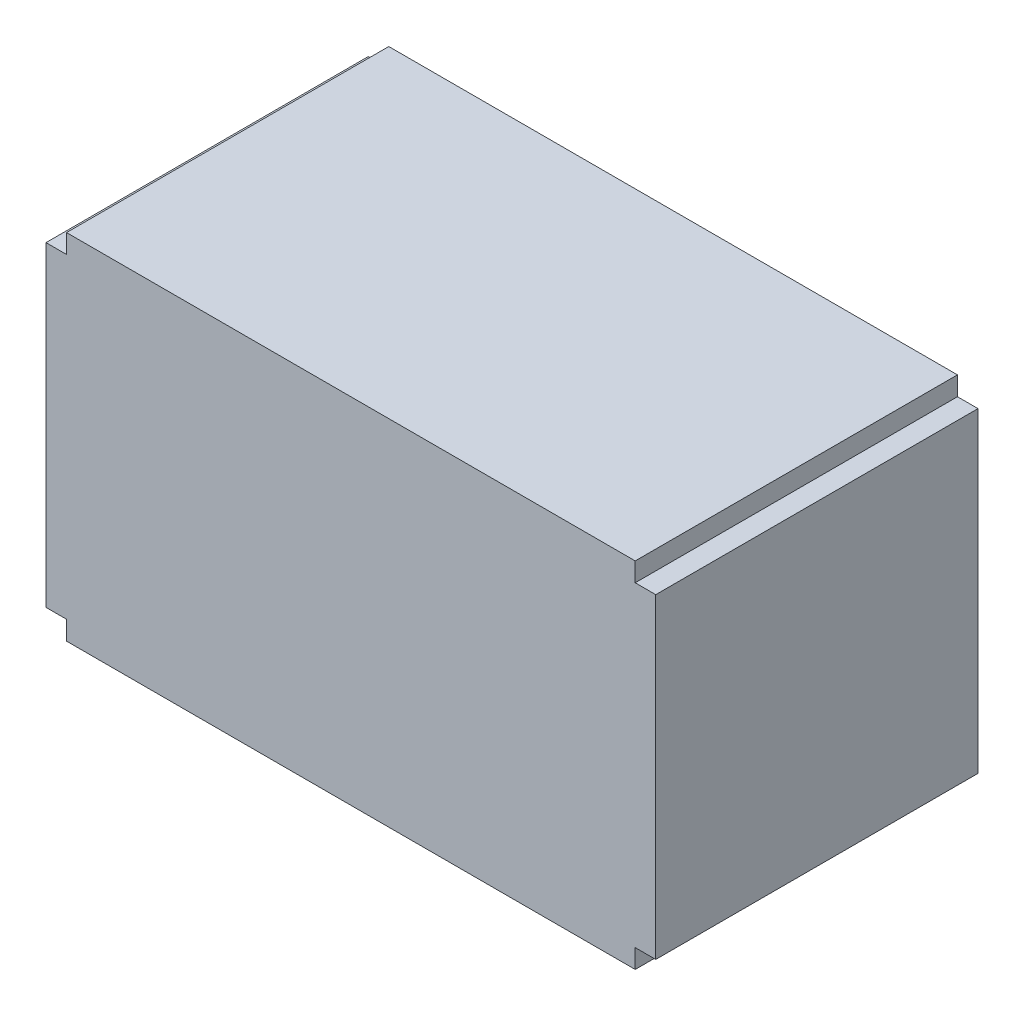
SolidWorks part; units mm, degrees
ref_plane "前视基准面" through (0, 0, 0) normal (0, 0, 1) x (1, 0, 0)
ref_plane "上视基准面" through (0, 0, 0) normal (0, 1, 0) x (1, 0, 0)
ref_plane "右视基准面" through (0, 0, 0) normal (1, 0, 0) x (0, 0, -1)
sketch "草图1" plane through (0, 0, 0) normal (0, 0, 1) x (1, 0, 0)
  line L0 (0.965, -0.5) -> (0.9, -0.5)
  line L1 (0.9, -0.5) -> (0.9, -0.56)
  line L2 (0.9, -0.56) -> (-0.9, -0.56)
  line L3 (-0.9, -0.56) -> (-0.9, -0.5)
  line L4 (-0.9, -0.5) -> (-0.965, -0.5)
  line L5 (-0.965, -0.5) -> (-0.965, 0.5)
  line L6 (-0.965, 0.5) -> (-0.9, 0.5)
  line L7 (-0.9, 0.5) -> (-0.9, 0.56)
  line L8 (-0.9, 0.56) -> (0.9, 0.56)
  line L9 (0.9, 0.56) -> (0.9, 0.5)
  line L10 (0.9, 0.5) -> (0.965, 0.5)
  line L11 (0.965, 0.5) -> (0.965, -0.5)
extrude "Component_Outline" add sketch "草图1" along normal blind 1.02 separate body
sketch3d "3D草图1"
  line L0 (0, 0, 0) -> (1, 0, 0)
  line L1 (0, 0, 0) -> (0, 1, 0)
  line L2 (0, 0, 0) -> (0, 0, 1)
  point P0 (0, 0, 0)
